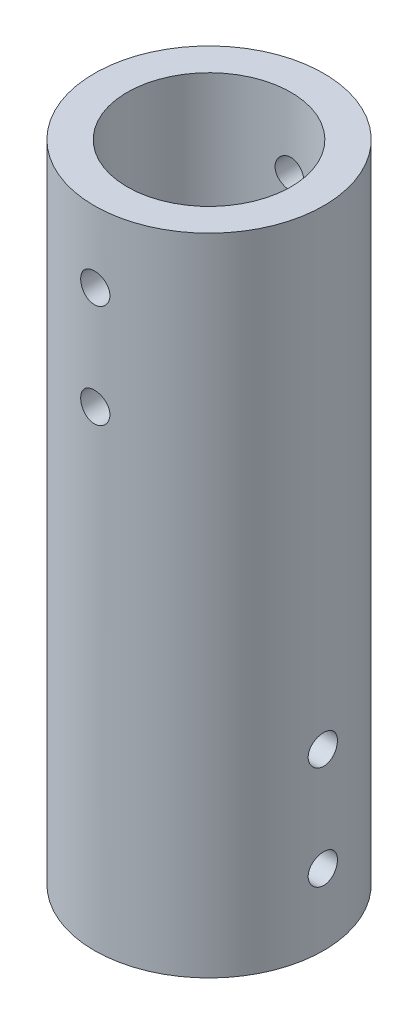
SolidWorks part; units mm, degrees
material "PVC Rigid"
ref_plane "Front Plane" through (0, 0, 0) normal (0, 0, 1) x (1, 0, 0)
ref_plane "Top Plane" through (0, 0, 0) normal (0, 1, 0) x (1, 0, 0)
ref_plane "Right Plane" through (0, 0, 0) normal (1, 0, 0) x (0, 0, -1)
sketch "Sketch1" plane through (0, 0, 0) normal (0, 1, 0) x (1, 0, 0)
  circle A0 centre (0, 0) radius 13.335
  circle A1 centre (0, 0) radius 9.525
  dimension "D1" = 26.67
  dimension "D2" = 19.05
extrude "Boss-Extrude1" add sketch "Sketch1" along normal blind 75
sketch "Sketch4" plane through (0, 0, 0) normal (0, 0, 1) x (1, 0, 0)
  line L0 (0, 75) -> (0, 54.7442) construction
  line L1 (9.525, 75) -> (-9.525, 75) construction
  line L2 (13.335, 75) -> (-13.335, 75) construction
  circle A0 centre (0, 66.7442) radius 1.7
  circle A1 centre (0, 54.7442) radius 1.7
  circle A3 centre (0, 54.7442) radius 1.7 construction
  dimension "D1" = 3.4
  dimension "D2" = 3.4
  dimension "D3" = 8.2558
  dimension "D4" = 12
extrude "Cut-Extrude1" cut sketch "Sketch4" against normal through all both and the other way through all
sketch "Sketch6" plane through (0, 0, 0) normal (0, 0, 1) x (1, 0, 0)
  line L0 (13.335, 75) -> (13.335, 0) construction
  line L1 (13.335, 75) -> (-13.335, 75) construction
  line L2 (-13.335, 0) -> (13.335, 0) construction
  line L3 (13.335, 37.5) -> (-13.335, 37.5) construction
  line L4 (-13.335, 75) -> (-13.335, 0) construction
  line L5 (13.335, 0) -> (13.335, 75) construction
sketch "Sketch7" plane through (0, 0, 0) normal (1, 0, 0) x (0, 0, -1)
  line L0 (0, 0) -> (0, 20.26) construction
  circle A0 centre (0, 8.26) radius 1.7
  circle A1 centre (0, 20.26) radius 1.7
  dimension "D1" = 3.4
  dimension "D2" = 12
  dimension "D3" = 8.26
extrude "Cut-Extrude2" cut sketch "Sketch7" against normal through all both and the other way through all
